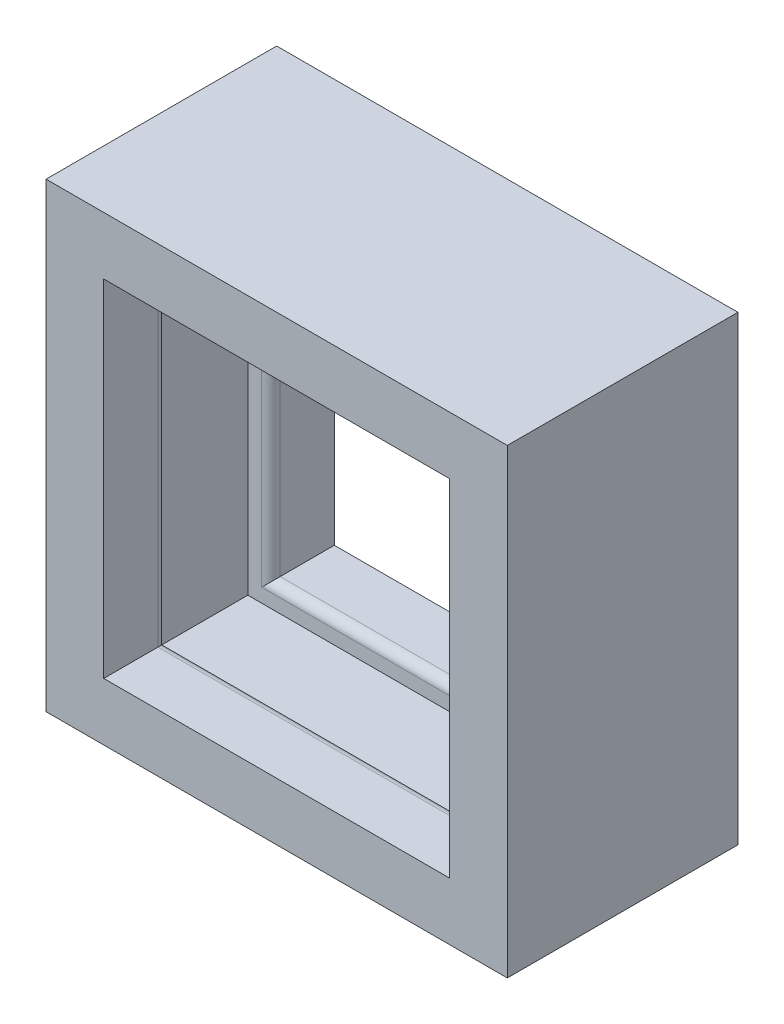
SolidWorks part; units mm, degrees
ref_plane "Front Plane" through (0, 0, 0) normal (0, 0, 1) x (1, 0, 0)
ref_plane "Top Plane" through (0, 0, 0) normal (0, 1, 0) x (1, 0, 0)
ref_plane "Right Plane" through (0, 0, 0) normal (1, 0, 0) x (0, 0, -1)
sketch "Sketch1" plane through (0, 0, 0) normal (0, 0, 1) x (1, 0, 0)
  line L1 (-100, -100) -> (100, -100)
  line L2 (-100, -100) -> (-100, 100)
  line L3 (-100, 100) -> (100, 100)
  line L4 (100, -100) -> (100, 100)
  line L5 (-100, -100) -> (100, 100) construction
  line L6 (-100, 100) -> (100, -100) construction
  line L7 (-75, 75) -> (75, 75)
  line L8 (-75, 75) -> (-75, -75)
  line L9 (-75, -75) -> (75, -75)
  line L10 (75, 75) -> (75, -75)
  line L11 (-75, 75) -> (75, -75) construction
  line L12 (-75, -75) -> (75, 75) construction
  point P0 (0, 0)
  point P6 (0, 0)
  point P11 (75, -75)
  dimension "D1" = 200
  dimension "D2" = 200
  dimension "D3" = 25
extrude "Boss-Extrude1" add sketch "Sketch1" along normal mid plane 100
sketch "Sketch2" plane through (0, 0, 0) normal (0, 0, 1) x (1, 0, 0)
  line L0 (-100, 100) -> (-100, -100) construction
  line L1 (-85, 85) -> (85, 85)
  line L2 (-85, 85) -> (-85, -85)
  line L3 (-85, -85) -> (85, -85)
  line L4 (85, 85) -> (85, -85)
  line L5 (-85, 85) -> (85, -85) construction
  line L6 (-85, -85) -> (85, 85) construction
  point P0 (0, 0)
  dimension "D1" = 15
extrude "Cut-Extrude1" cut sketch "Sketch2" against normal mid plane 45
fillet "Fillet1" radius 4 4 edges at (0, 75, -22.5) (-75, 0, -22.5) (75, 0, -22.5) (0, -75, -22.5)
fillet "Fillet2" radius 4 4 edges at (0, 75, 22.5) (75, 0, 22.5) (-75, 0, 22.5) (0, -75, 22.5)
